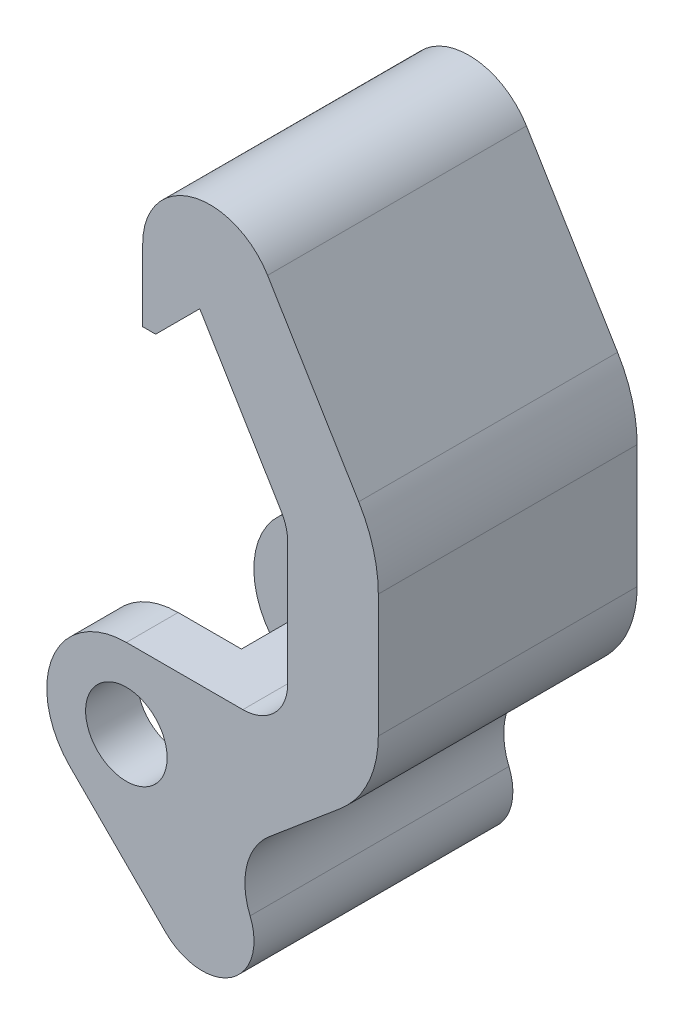
SolidWorks part; units mm, degrees
ref_plane "Front" through (0, 0, 0) normal (0, 0, 1) x (1, 0, 0)
ref_plane "Top" through (0, 0, 0) normal (0, 1, 0) x (1, 0, 0)
ref_plane "Right" through (0, 0, 0) normal (1, 0, 0) x (0, 0, -1)
sketch "Sketch1" plane through (0, 0, 0) normal (0, 0, 1) x (1, 0, 0)
  line L3 (9.7325, 4.8075) -> (9.7325, 9.5575)
  line L6 (-1.575, 0) -> (-3.075, 0) construction
  line L7 (8.9761, 12.2673) -> (5.4556, 18.0825)
  line L10 (0.6312, 16.736) -> (0.6312, 13.9501)
  line L13 (2.8347, 15.6536) -> (5.9821, 10.4547)
  line L14 (6.2325, 9.5575) -> (6.2325, 4.8075)
  line L15 (4.5, 3.075) -> (0, 3.075)
  line L16 (0.6312, 13.9501) -> (1.1312, 13.9501)
  line L17 (1.1312, 13.9501) -> (2.8347, 15.6536)
  line L19 (-2.1744, -2.1744) -> (1.5171, -5.8658)
  line L22 (8.2605, 1.6431) -> (5.5133, -0.6707)
  circle A0 centre (0, 0) radius 1.575
  circle A3 centre (0, 0) radius 3.075 construction
  arc A11 (9.7325, 9.5575) -> (8.9761, 12.2673) centre (4.5, 9.5575) ccw
  arc A12 (5.4556, 18.0825) -> (0.6312, 16.736) centre (3.2314, 16.736) ccw
  arc A15 (5.9821, 10.4547) -> (6.2325, 9.5575) centre (4.5, 9.5575) cw
  arc A16 (6.2325, 4.8075) -> (4.5, 3.075) centre (4.5, 4.8075) cw
  arc A17 (0, 3.075) -> (-2.1744, -2.1744) centre (0, 0) ccw
  arc A18 (1.5171, -5.8658) -> (4.7789, -3.6857) centre (2.9313, -4.4516) ccw
  arc A19 (4.7789, -3.6857) -> (5.5133, -0.6707) centre (7.2055, -2.6799) cw
  arc A21 (8.2605, 1.6431) -> (9.7325, 4.8075) centre (5.5953, 4.8075) ccw
  point P3 (8.2106, 1.9946)
  point P33 (5.0837, -1.0326)
  point P34 (3.0351, -4.5553)
  point P35 (4.5, -4.0203)
  point P36 (9.7325, 4.8075)
  point P37 (0, 0)
  point P38 (4.7789, -3.6857)
  dimension "D1" = 3.15
  dimension "D9" = 2
  dimension "D2" = 1.5
  dimension "D4" = 45
  dimension "D5" = 0.5
  dimension "D3" = 3.5
  dimension "D7" = 4.5
  dimension "D8" = 4.75
  dimension "D6" = 45
extrude "Boss-Extrude1" add sketch "Sketch1" along normal mid plane 10
sketch "Sketch2" plane through (0, 0, 0) normal (0, 0, 1) x (1, 0, 0)
  circle A0 centre (0, 0) radius 3.9286
extrude "Cut-Extrude1" cut sketch "Sketch2" against normal mid plane 6
equation "\"D1@Sketch1\"=\"Hardware Clearance Hole Diameter@Box Assy.Assembly\""
